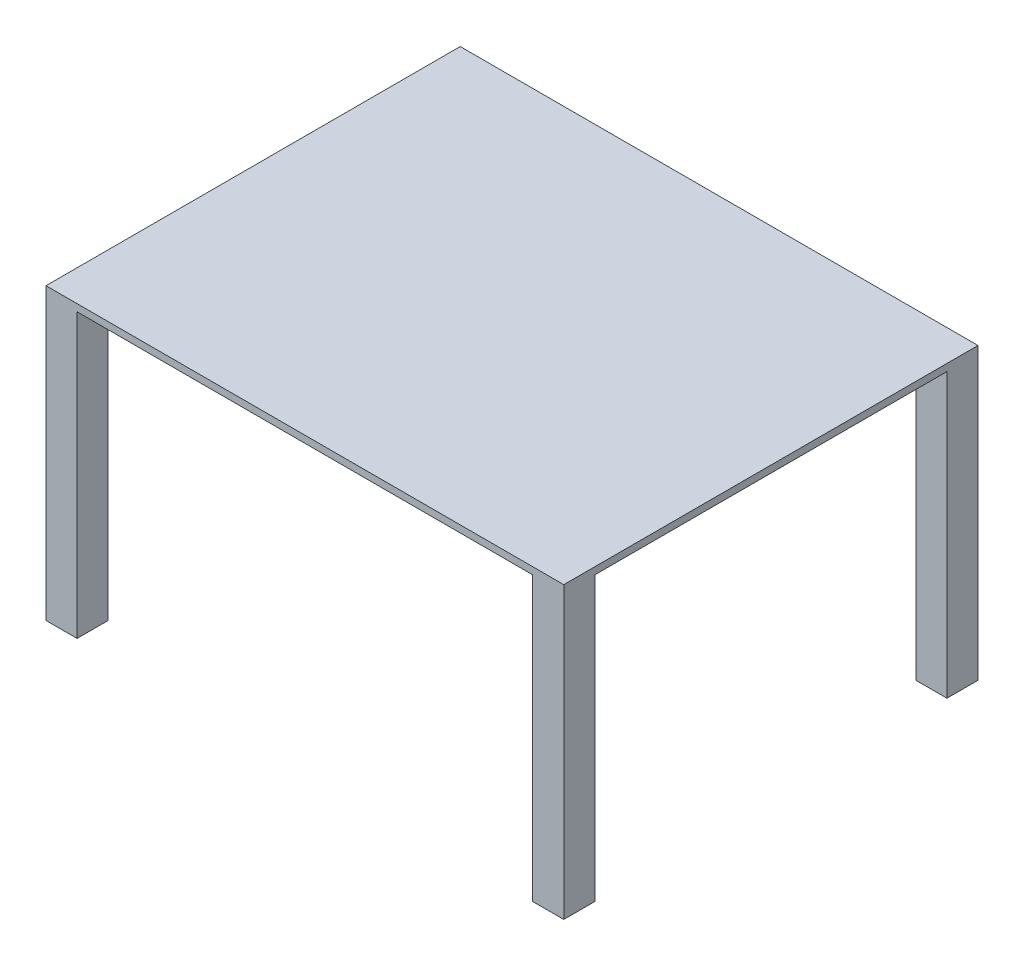
SolidWorks part; units mm, degrees
ref_plane "Alzado" through (0, 0, 0) normal (0, 0, 1) x (1, 0, 0)
ref_plane "Planta" through (0, 0, 0) normal (0, 1, 0) x (1, 0, 0)
ref_plane "Vista lateral" through (0, 0, 0) normal (1, 0, 0) x (0, 0, -1)
sketch "Croquis1" plane through (0, 0, 0) normal (0, 1, 0) x (1, 0, 0)
  line L1 (625, -500) -> (-625, -500)
  line L2 (625, -500) -> (625, 500)
  line L3 (625, 500) -> (-625, 500)
  line L4 (-625, -500) -> (-625, 500)
  line L5 (625, -500) -> (-625, 500) construction
  line L6 (625, 500) -> (-625, -500) construction
  point P0 (0, 0)
  dimension "D1" = 1250
  dimension "D2" = 1000
extrude "Saliente-Extruir1" add sketch "Croquis1" along normal blind 17
sketch "Croquis2" plane through (0, 17, 0) normal (0, 1, 0) x (1, 0, 0)
  line L1 (-625, -500) -> (-550, -500)
  line L2 (-625, -500) -> (-625, -425)
  line L3 (-625, -425) -> (-550, -425)
  line L4 (-550, -500) -> (-550, -425)
  line L5 (-625, 500) -> (-550, 500)
  line L6 (-625, 500) -> (-625, 425)
  line L7 (-625, 425) -> (-550, 425)
  line L8 (-550, 500) -> (-550, 425)
  line L9 (625, -500) -> (550, -500)
  line L10 (625, -500) -> (625, -425)
  line L11 (625, -425) -> (550, -425)
  line L12 (550, -500) -> (550, -425)
  line L13 (625, 500) -> (550, 500)
  line L14 (625, 500) -> (625, 425)
  line L15 (625, 425) -> (550, 425)
  line L16 (550, 500) -> (550, 425)
  dimension "D1" = 75
  dimension "D2" = 75
  dimension "D3" = 75
  dimension "D4" = 75
  dimension "D5" = 75
  dimension "D6" = 75
  dimension "D7" = 75
  dimension "D8" = 75
extrude "Saliente-Extruir2" add sketch "Croquis2" against normal blind 700
sketch "Croquis3" plane through (0, 17, 0) normal (0, 1, 0) x (1, 0, 0)
  line L2 (0, -500) -> (0, -480) construction
  line L3 (-625, -500) -> (625, -500) construction
  dimension "D1" = 20
